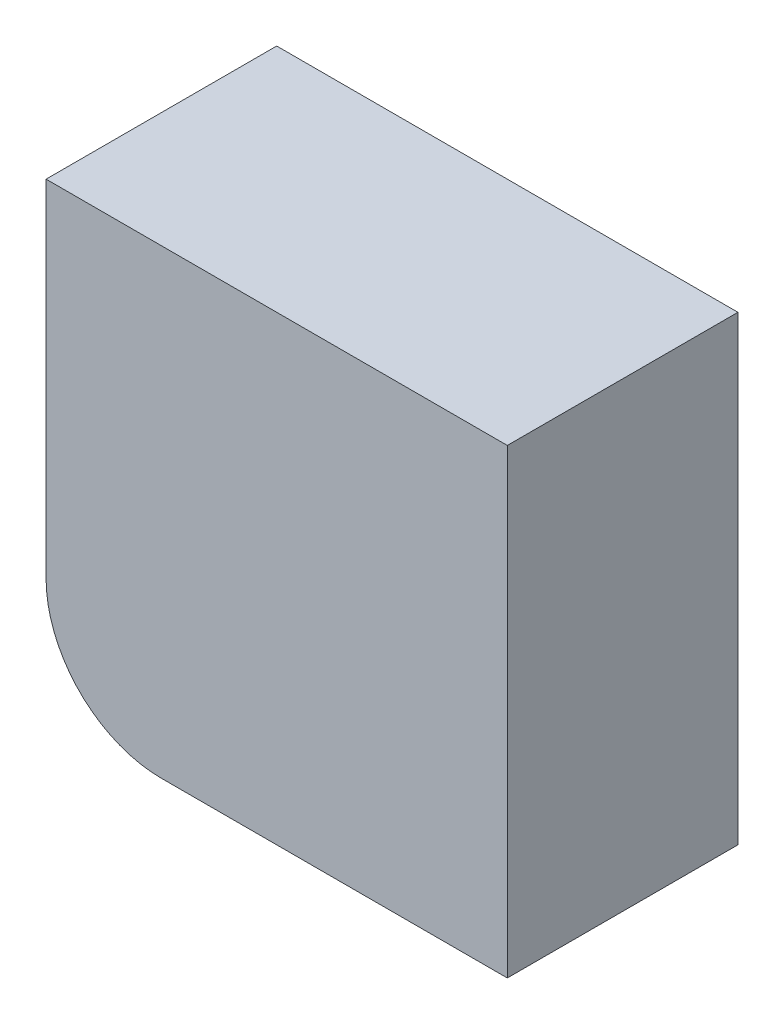
SolidWorks part; units mm, degrees
ref_plane "前视基准面" through (0, 0, 0) normal (0, 0, 1) x (1, 0, 0)
ref_plane "上视基准面" through (0, 0, 0) normal (0, 1, 0) x (1, 0, 0)
ref_plane "右视基准面" through (0, 0, 0) normal (1, 0, 0) x (0, 0, -1)
other "Configuration Table"
sketch "草图1" plane through (0, 0, 0) normal (0, 0, 1) x (1, 0, 0)
  line L1 (0, 0) -> (20, 0)
  line L2 (0, 0) -> (0, 20)
  line L3 (0, 20) -> (20, 20)
  line L4 (20, 0) -> (20, 20)
extrude "BaseBox" add sketch "草图1" along normal blind 10
fillet "FaceFillet" radius 5 1 edges at (0, 0, 5)
